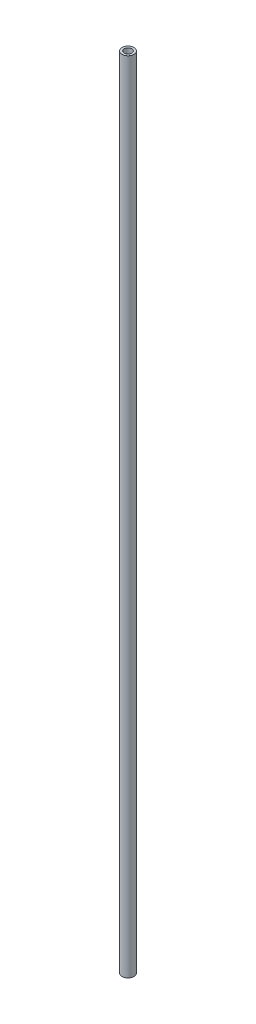
SolidWorks part; units mm, degrees
ref_plane "Front" through (0, 0, 0) normal (0, 0, 1) x (1, 0, 0)
ref_plane "Top" through (0, 0, 0) normal (0, 1, 0) x (1, 0, 0)
ref_plane "Right" through (0, 0, 0) normal (1, 0, 0) x (0, 0, -1)
sketch "Sketch1" plane through (0, 0, 0) normal (0, 1, 0) x (1, 0, 0)
  circle A0 centre (0, 0) radius 1
  dimension "D1" = 2
extrude "Boss-Extrude1" add sketch "Sketch1" along normal blind 133.2
sketch "Sketch2" plane through (0, 133.2, 0) normal (0, 1, 0) x (1, 0, 0)
  line L0 (0, -1) -> (0, 1) construction
  circle A0 centre (0, 0) radius 1 construction
  point P7 (0, 0)
sketch "Sketch3" plane through (0, 0, 0) normal (0, -1, 0) x (1, 0, 0)
  line L0 (0, -1) -> (0, 1) construction
  circle A0 centre (0, 0) radius 1 construction
  point P7 (0, 0)
hole_wizard "M1.6x0.35 Tapped Hole1" positions "3DSketch1" profile "Sketch4" tap size "M1.6x0.35" standard "ANSI Metric"
sketch3d "3DSketch1"
  line L0 (0, 133.2, 0) -> (0, 0, 0) construction
  line L1 (0, 0, -1) -> (0, 0, 1) construction
  point P0 (0, 133.2, 0)
  point P3 (0, 0, 0)
  point P6 (0, 0, 0)
  point P9 (0, 0, 0)
  point P13 (0, 0, 0)
sketch "Sketch4" plane through (0, 133.2, 0) normal (1, 0, 0) x (0, 0, 1)
  line L0 (0, 0) -> (0, 6.3755)
  line L1 (0, 6.3755) -> (0.625, 6)
  line L2 (0.625, 6) -> (0.625, 0)
  line L5 (0.625, 0) -> (0, 0)
  line L10 (0, 6.3755) -> (-0.625, 6) construction
  line L11 (0, -6.35) -> (0, 107.95) construction
  dimension "Tap Drill Dia." = 1.25
  dimension "Tap Drill Depth" = 6
  dimension "Drill Angle" = 118
cosmetic thread "Hole Thread16" parameters "D1"=3.2, "D2"=1.6
ref_plane "Plane1" through (0, 66.6, 0) normal (0, -1, 0) x (-1, 0, 0)
mirror "Mirror1" about plane through (0, 66.6, 0) normal (0, -1, 0) of "M1.6x0.35 Tapped Hole1"
cosmetic thread "Hole Thread17" parameters "D1"=3.2, "D2"=1.6
